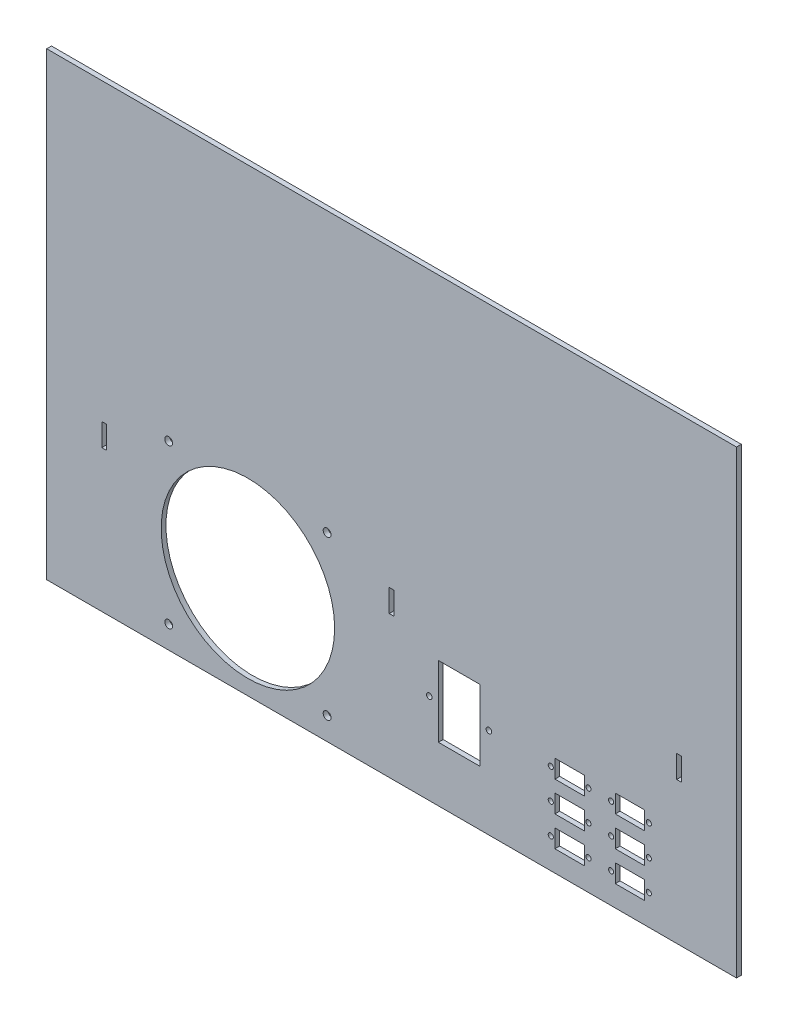
SolidWorks part; units mm, degrees
ref_plane "Front Plane" through (0, 0, 0) normal (0, 0, 1) x (1, 0, 0)
ref_plane "Top Plane" through (0, 0, 0) normal (0, 1, 0) x (1, 0, 0)
ref_plane "Right Plane" through (0, 0, 0) normal (1, 0, 0) x (0, 0, -1)
sketch "Sketch1" plane through (0, 0, 0) normal (0, 0, 1) x (1, 0, 0)
  line L1 (-228.6, -152.4) -> (228.6, -152.4)
  line L2 (-228.6, -152.4) -> (-228.6, 152.4)
  line L3 (-228.6, 152.4) -> (228.6, 152.4)
  line L4 (228.6, -152.4) -> (228.6, 152.4)
  line L5 (-228.6, -152.4) -> (228.6, 152.4) construction
  line L6 (-228.6, 152.4) -> (228.6, -152.4) construction
  point P0 (0, 0)
  dimension "D1" = 304.8
  dimension "D2" = 457.2
extrude "Acrylic Panel" add sketch "Sketch1" along normal blind 3.175 contours L3 L4 L1 L2
sketch "Sketch2" plane through (0, 0, 3.175) normal (0, 0, 1) x (1, 0, 0)
  line L0 (-228.6, -152.4) -> (228.6, -152.4) construction
  line L1 (-147.75, -32.4) -> (-42.75, -32.4) construction
  line L2 (-147.75, -32.4) -> (-147.75, -137.4) construction
  line L3 (-147.75, -137.4) -> (-42.75, -137.4) construction
  line L4 (-42.75, -32.4) -> (-42.75, -137.4) construction
  line L5 (0, 0) -> (0, -28.1478) construction
  line L6 (-1.5875, -43.3) -> (1.5875, -43.3)
  line L7 (-1.5875, -43.3) -> (-1.5875, -58.3)
  line L8 (-1.5875, -58.3) -> (1.5875, -58.3)
  line L9 (1.5875, -43.3) -> (1.5875, -58.3)
  line L10 (188.9125, -43.3) -> (192.0875, -43.3)
  line L11 (188.9125, -43.3) -> (188.9125, -58.3)
  line L12 (188.9125, -58.3) -> (192.0875, -58.3)
  line L13 (192.0875, -43.3) -> (192.0875, -58.3)
  line L14 (228.6, -152.4) -> (228.6, 152.4) construction
  line L15 (-192.0875, -43.3) -> (-192.0875, -58.3)
  line L16 (-188.9125, -58.3) -> (-192.0875, -58.3)
  line L17 (-188.9125, -43.3) -> (-188.9125, -58.3)
  line L18 (-188.9125, -43.3) -> (-192.0875, -43.3)
  line L19 (-188.9125, -50.8) -> (-1.5875, -50.8) construction
  line L20 (-147.75, -32.4) -> (-42.75, -137.4) construction
  line L21 (105.5, -132.4) -> (130.5, -132.4) construction
  line L22 (108.25, -138.4) -> (127.75, -138.4)
  line L23 (108.25, -138.4) -> (108.25, -126.4)
  line L24 (108.25, -126.4) -> (127.75, -126.4)
  line L25 (127.75, -138.4) -> (127.75, -126.4)
  line L26 (148.25, -126.4) -> (167.75, -126.4)
  line L27 (148.25, -138.4) -> (148.25, -126.4)
  line L28 (167.75, -138.4) -> (167.75, -126.4)
  line L29 (148.25, -138.4) -> (167.75, -138.4)
  line L30 (148.25, -106.4) -> (167.75, -106.4)
  line L31 (148.25, -118.4) -> (148.25, -106.4)
  line L32 (167.75, -118.4) -> (167.75, -106.4)
  line L33 (148.25, -118.4) -> (167.75, -118.4)
  line L34 (148.25, -86.4) -> (167.75, -86.4)
  line L35 (148.25, -98.4) -> (148.25, -86.4)
  line L36 (167.75, -98.4) -> (167.75, -86.4)
  line L37 (148.25, -98.4) -> (167.75, -98.4)
  line L38 (108.25, -106.4) -> (127.75, -106.4)
  line L39 (108.25, -118.4) -> (108.25, -106.4)
  line L40 (127.75, -118.4) -> (127.75, -106.4)
  line L41 (108.25, -118.4) -> (127.75, -118.4)
  line L42 (108.25, -86.4) -> (127.75, -86.4)
  line L43 (108.25, -98.4) -> (108.25, -86.4)
  line L44 (127.75, -98.4) -> (127.75, -86.4)
  line L45 (108.25, -98.4) -> (127.75, -98.4)
  line L46 (25, -92.4) -> (64.5, -92.4) construction
  line L48 (31, -115.9) -> (58.5, -115.9)
  line L49 (31, -115.9) -> (31, -68.9)
  line L50 (31, -68.9) -> (58.5, -68.9)
  line L51 (58.5, -115.9) -> (58.5, -68.9)
  line L52 (31, -115.9) -> (58.5, -68.9) construction
  line L53 (31, -68.9) -> (58.5, -115.9) construction
  circle A0 centre (-147.75, -32.4) radius 2.6
  circle A1 centre (-42.75, -32.4) radius 2.6
  circle A2 centre (-147.75, -137.4) radius 2.6
  circle A3 centre (-42.75, -137.4) radius 2.6
  circle A4 centre (-95.25, -84.9) radius 57.5
  circle A5 centre (25, -92.4) radius 1.85
  circle A6 centre (64.5, -92.4) radius 1.85
  circle A7 centre (105.5, -132.4) radius 1.7
  circle A8 centre (130.5, -132.4) radius 1.7
  circle A9 centre (145.5, -132.4) radius 1.7
  circle A10 centre (170.5, -132.4) radius 1.7
  circle A11 centre (145.5, -112.4) radius 1.7
  circle A12 centre (170.5, -112.4) radius 1.7
  circle A13 centre (145.5, -92.4) radius 1.7
  circle A14 centre (170.5, -92.4) radius 1.7
  circle A15 centre (105.5, -112.4) radius 1.7
  circle A16 centre (130.5, -112.4) radius 1.7
  circle A17 centre (105.5, -92.4) radius 1.7
  circle A18 centre (130.5, -92.4) radius 1.7
  point P8 (0, -43.3)
  point P9 (-1.5875, -50.8)
  point P23 (1.5875, -50.8)
  point P24 (188.9125, -50.8)
  point P25 (190.5, -43.3)
  point P34 (-95.25, -32.4)
  point P35 (-95.25, -50.8)
  point P46 (118, -138.4)
  point P47 (108.25, -132.4)
  point P48 (118, -132.4)
  point P69 (158, -118.4)
  point P70 (158, -126.4)
  point P71 (190.5, -58.3)
  point P72 (44.75, -92.4)
  point P78 (0, -58.3)
  dimension "D3" = 5.2
  dimension "D8" = 115
  dimension "D9" = 3.7
  dimension "D12" = 3.4
  dimension "D1" = 15
  dimension "D2" = 105
  dimension "D4" = 3.175
  dimension "D5" = 15
  dimension "D6" = 101.6
  dimension "D7" = 38.1
  dimension "D10" = 39.5
  dimension "D11" = 25
  dimension "D15" = 20
  dimension "D16" = 20
  dimension "D17" = 20
  dimension "D18" = 40
  dimension "D19" = 25
  dimension "D20" = 60
  dimension "D21" = 19.5
  dimension "D22" = 12
  dimension "D25" = 40
  dimension "D26" = 20
  dimension "D27" = 27.5
  dimension "D28" = 47
  dimension "D13" = 2
  dimension "D14" = 3
  dimension "D23" = 2
  dimension "D24" = 3
extrude "Cut-Extrude1" cut sketch "Sketch2" against normal through all
sketch "Sketch3" plane through (0, 0, 3.175) normal (0, 0, 1) x (1, 0, 0)
  line L0 (-214.1777, 130.1639) -> (-214.1777, 115.1639)
  line L1 (-214.1777, 115.1639) -> (-211.0027, 115.1639)
  line L2 (-211.0027, 115.1639) -> (-211.0027, 97.2639)
  line L3 (-211.0027, 97.2639) -> (-134.8027, 21.0639)
  line L4 (-214.1777, 130.1639) -> (-211.0027, 130.1639)
  line L5 (-211.0027, 130.1639) -> (-211.0027, 148.0639)
  line L6 (-211.0027, 148.0639) -> (-84.0027, 21.0639)
  line L7 (-84.0027, 21.0639) -> (-134.8027, 21.0639)
  line L8 (-1.5875, -43.3) -> (-1.5875, -58.3) construction
  line L9 (-152.7032, 130.1639) -> (-152.7032, 115.1639)
  line L10 (-152.7032, 115.1639) -> (-149.5282, 115.1639)
  line L11 (-228.6, 0) -> (228.6, 0)
  line L12 (-228.6, -152.4) -> (-228.6, 152.4) construction
  line L13 (228.6, -152.4) -> (228.6, 152.4) construction
  line L14 (-149.5282, 115.1639) -> (-149.5282, 97.2639)
  line L15 (-149.5282, 97.2639) -> (-73.3282, 21.0639)
  line L16 (-152.7032, 130.1639) -> (-149.5282, 130.1639)
  line L17 (-149.5282, 130.1639) -> (-149.5282, 148.0639)
  line L18 (-149.5282, 148.0639) -> (-22.5282, 21.0639)
  line L19 (-22.5282, 21.0639) -> (-73.3282, 21.0639)
  line L20 (-91.2287, 130.1639) -> (-91.2287, 115.1639)
  line L21 (-91.2287, 115.1639) -> (-88.0537, 115.1639)
  line L22 (-88.0537, 115.1639) -> (-88.0537, 97.2639)
  line L23 (-88.0537, 97.2639) -> (-11.8537, 21.0639)
  line L24 (-91.2287, 130.1639) -> (-88.0537, 130.1639)
  line L25 (-88.0537, 130.1639) -> (-88.0537, 148.0639)
  line L26 (-88.0537, 148.0639) -> (38.9463, 21.0639)
  line L27 (38.9463, 21.0639) -> (-11.8537, 21.0639)
  point P10 (-214.1777, 122.6639)
  point P17 (-149.5282, 148.0639)
  dimension "D1" = 3.175
  dimension "D2" = 50.8
  dimension "D3" = 101.6
  dimension "D4" = 135
  dimension "D5" = 3
